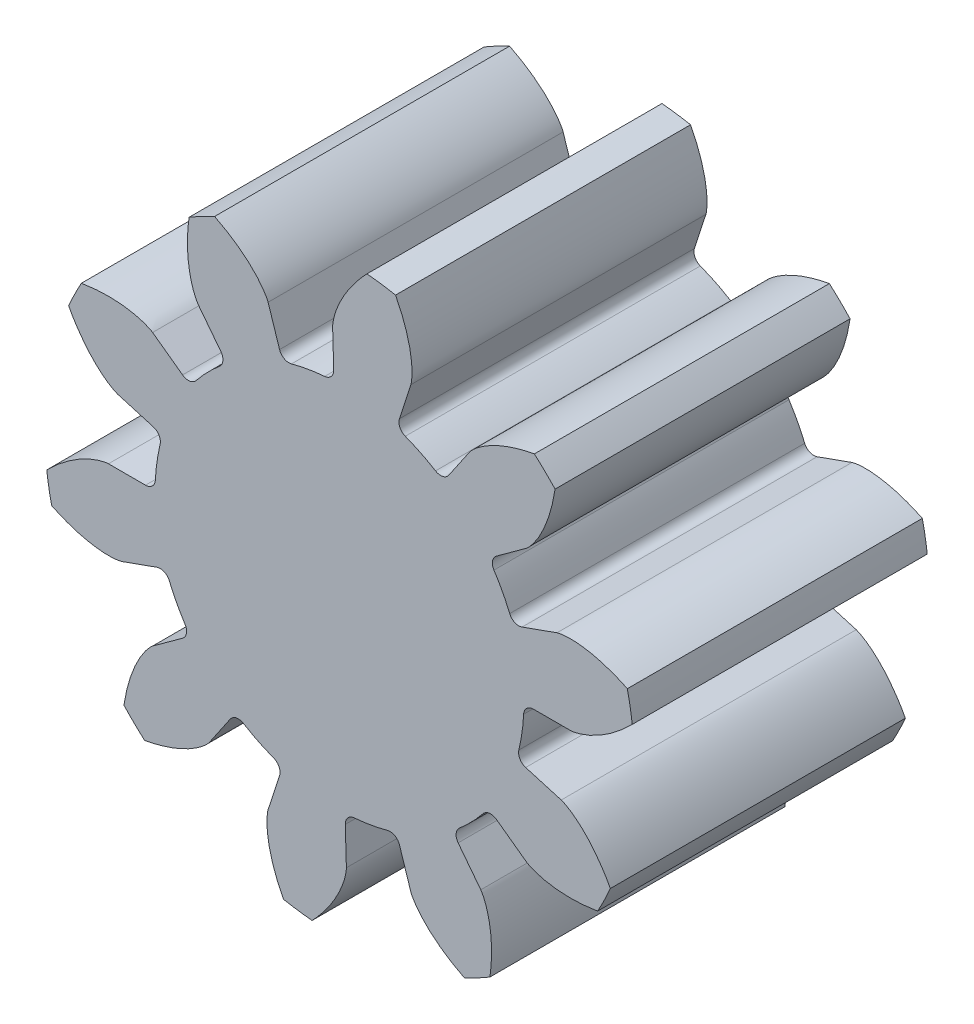
SolidWorks part; units mm, degrees
ref_plane "Front Plane" through (0, 0, 0) normal (0, 0, 1) x (1, 0, 0)
ref_plane "Top Plane" through (0, 0, 0) normal (0, 1, 0) x (1, 0, 0)
ref_plane "Right Plane" through (0, 0, 0) normal (1, 0, 0) x (0, 0, -1)
sketch "Sketch1" plane through (0, 0, 0) normal (0, 0, 1) x (1, 0, 0)
  circle A0 centre (0, 0) radius 3
  dimension "D1" = 6
extrude "Boss-Extrude1" add sketch "Sketch1" along normal blind 3
sketch "Sketch3" plane through (0, 0, 0) normal (0, 0, 1) x (1, 0, 0)
  line L0 (1.875, 0) -> (2.3492, 0)
  line L2 (1.7997, -0.526) -> (2.2549, -0.659)
  line L3 (0, 0) -> (2.9697, -0.4251) construction
  circle A0 centre (0, 0) radius 2.5 construction
  circle A1 centre (0, 0) radius 2.3492 construction
  arc A2 (1.7997, -0.526) -> (1.875, 0) centre (0, 0) ccw
  circle A3 centre (0, 0) radius 3 construction
  spline S0 degree 4 poles (2.3492, 0) (2.3523, 0.0001) (2.3582, 0.0005) (2.3678, 0.0015) (2.3867, 0.0043) (2.4078, 0.0086) (2.4315, 0.0146) (2.4568, 0.0221) (2.4783, 0.0293) (2.4996, 0.0371) (2.5206, 0.0454) (2.5459, 0.0561) (2.5759, 0.07) (2.6106, 0.0875) (2.6494, 0.1089) (2.6883, 0.1324) (2.7261, 0.1568) (2.7636, 0.1831) (2.7993, 0.2095) (2.8357, 0.2385) (2.869, 0.2661) (2.9053, 0.2986) (2.9344, 0.3253) (2.9717, 0.3622) (2.9935, 0.3845) (3.0186, 0.4112) (3.0295, 0.4234) (3.0363, 0.4309) knots 0 0 0 0 0 0.015084 0.028532 0.04661 0.092111 0.119476 0.146842 0.174209 0.201575 0.228941 0.256307 0.307035 0.361767 0.4165 0.471232 0.525964 0.580697 0.635429 0.690161 0.744894 0.799626 0.854358 0.909091 0.954545 1 1 1 1 1 construction
  spline S1 degree 4 poles (2.3492, 0) (2.3523, 0.0001) (2.3582, 0.0005) (2.3678, 0.0015) (2.3867, 0.0043) (2.4078, 0.0086) (2.4315, 0.0146) (2.4568, 0.0221) (2.4783, 0.0293) (2.4996, 0.0371) (2.5206, 0.0454) (2.5459, 0.0561) (2.5759, 0.07) (2.6106, 0.0875) (2.6494, 0.1089) (2.6883, 0.1324) (2.7261, 0.1568) (2.7636, 0.1831) (2.7993, 0.2095) (2.8357, 0.2385) (2.869, 0.2661) (2.9053, 0.2986) (2.9344, 0.3253) (2.9636, 0.3542) (2.9777, 0.3685) (2.9849, 0.3759) knots 0 0 0 0 0 0.015084 0.028532 0.04661 0.092111 0.119476 0.146842 0.174209 0.201575 0.228941 0.256307 0.307035 0.361767 0.4165 0.471232 0.525964 0.580697 0.635429 0.690161 0.744894 0.799626 0.854358 0.909091 0.909091 0.909091 0.909091 0.909091
  spline S2 degree 4 poles (2.2549, -0.659) (2.2579, -0.66) (2.2634, -0.662) (2.2723, -0.6656) (2.2896, -0.6736) (2.3087, -0.6837) (2.3298, -0.6961) (2.352, -0.7105) (2.3706, -0.7234) (2.3888, -0.7368) (2.4066, -0.7507) (2.4279, -0.7681) (2.4529, -0.7898) (2.4813, -0.8163) (2.5125, -0.8478) (2.5433, -0.8812) (2.5726, -0.9153) (2.6012, -0.951) (2.6282, -0.9864) (2.655, -1.0245) (2.6791, -1.0602) (2.7049, -1.1016) (2.7253, -1.1354) (2.7508, -1.1813) (2.7654, -1.2089) (2.782, -1.2415) (2.7891, -1.2563) (2.7935, -1.2654) knots 0 0 0 0 0 0.015084 0.028532 0.04661 0.092111 0.119476 0.146842 0.174209 0.201575 0.228941 0.256307 0.307035 0.361767 0.4165 0.471232 0.525964 0.580697 0.635429 0.690161 0.744894 0.799626 0.854358 0.909091 0.954545 1 1 1 1 1 construction
  spline S3 degree 4 poles (2.2549, -0.659) (2.2579, -0.66) (2.2634, -0.662) (2.2723, -0.6656) (2.2896, -0.6736) (2.3087, -0.6837) (2.3298, -0.6961) (2.352, -0.7105) (2.3706, -0.7234) (2.3888, -0.7368) (2.4066, -0.7507) (2.4279, -0.7681) (2.4529, -0.7898) (2.4813, -0.8163) (2.5125, -0.8478) (2.5433, -0.8812) (2.5726, -0.9153) (2.6012, -0.951) (2.6282, -0.9864) (2.655, -1.0245) (2.6791, -1.0602) (2.7049, -1.1016) (2.7253, -1.1354) (2.7453, -1.1714) (2.7548, -1.189) (2.7596, -1.1981) knots 0 0 0 0 0 0.015084 0.028532 0.04661 0.092111 0.119476 0.146842 0.174209 0.201575 0.228941 0.256307 0.307035 0.361767 0.4165 0.471232 0.525964 0.580697 0.635429 0.690161 0.744894 0.799626 0.854358 0.909091 0.909091 0.909091 0.909091 0.909091
  point P5 (1.875, 0)
  point P11 (1.7997, -0.526)
  dimension "D1" = 5
  dimension "D2" = 4.6985
  dimension "D3" = 3.75
  dimension "D4" = 8.146
  dimension "D5" = 8.146
extrude "Cut-Extrude1" cut sketch "Sketch3" against normal through all and the other way through all
fillet "Fillet1" radius 0.1 1 edges at (1.7997, -0.526, 1.5)
fillet "Fillet2" radius 0.1 1 edges at (1.875, 0, 1.5)
pattern_circular "CirPattern14" count 10 over 360 about axis through (0, 0, 3) along (0, 0, -1) of "Cut-Extrude1", "Fillet1", "Fillet2"
equation "\"P\"= 2'Diametral Pitch"
equation "\"N\"= 10'Number of teeth"
equation "\"phi\"= 20deg'pressure angle"
equation "\"a\"= 1 / \"P\"'addendum"
equation "\"b\"= 1.25 / \"P\"'dedendum"
equation "\"c\"= \"b\" - \"a\"'clearance"
equation "\"dp\"= \"N\" / \"P\"'pitch circle diameter"
equation "\"db\"= \"dp\" * cos ( \"phi\" )'base circle diameter"
equation "\"D1@Sketch1\"= \"dp\" + 2 * \"a\"'Addendum circle diameter"
equation "\"D1@Sketch3\"= \"dp\"'pitch circle"
equation "\"D2@Sketch3\"= \"db\" 'base circle"
equation "\"D3@Sketch3\" = \"dp\" - 2 * \"b\"'dedendum circle"
equation "\"alpha\"= sqr ( \"dp\" ^ 2 - \"db\" ^ 2 ) / \"db\" * 180 / pi - \"phi\"'alpha (deg)"
equation "\"beta\"= ( 360 / ( 4 * \"N\" ) - \"alpha\" ) * 2"
equation "\"D4@Sketch3\"= 360 / ( 4 * \"N\" ) - \"alpha\""
equation "\"D5@Sketch3\"= 360 / ( 4 * \"N\" ) - \"alpha\""
